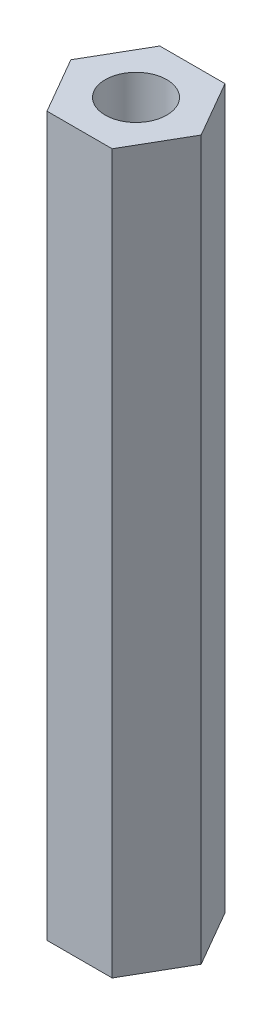
SolidWorks part; units mm, degrees
ref_plane "Front Plane" through (0, 0, 0) normal (0, 0, 1) x (1, 0, 0)
ref_plane "Top Plane" through (0, 0, 0) normal (0, 1, 0) x (1, 0, 0)
ref_plane "Right Plane" through (0, 0, 0) normal (1, 0, 0) x (0, 0, -1)
sketch "Sketch1" plane through (0, 0, 0) normal (0, 1, 0) x (1, 0, 0)
  line L1 (3.1754, 0) -> (1.5877, 2.75)
  line L2 (1.5877, 2.75) -> (-1.5877, 2.75)
  line L3 (-1.5877, 2.75) -> (-3.1754, 0)
  line L4 (-3.1754, 0) -> (-1.5877, -2.75)
  line L5 (-1.5877, -2.75) -> (1.5877, -2.75)
  line L6 (1.5877, -2.75) -> (3.1754, 0)
  circle A0 centre (0, 0) radius 2.75 construction
  dimension "D1" = 5.5
extrude "Boss-Extrude1" add sketch "Sketch1" along normal blind 35
sketch "Sketch2" plane through (0, 35, 0) normal (0, 1, 0) x (1, 0, 0)
  circle A0 centre (0, 0) radius 1.5
  dimension "D1" = 3
extrude "Cut-Extrude1" cut sketch "Sketch2" against normal blind 10
ref_plane "Plane1" through (0, 17.5, 0) normal (0, -1, 0) x (-1, 0, 0)
mirror "Mirror1" about plane through (0, 17.5, 0) normal (0, -1, 0) of "Cut-Extrude1"
